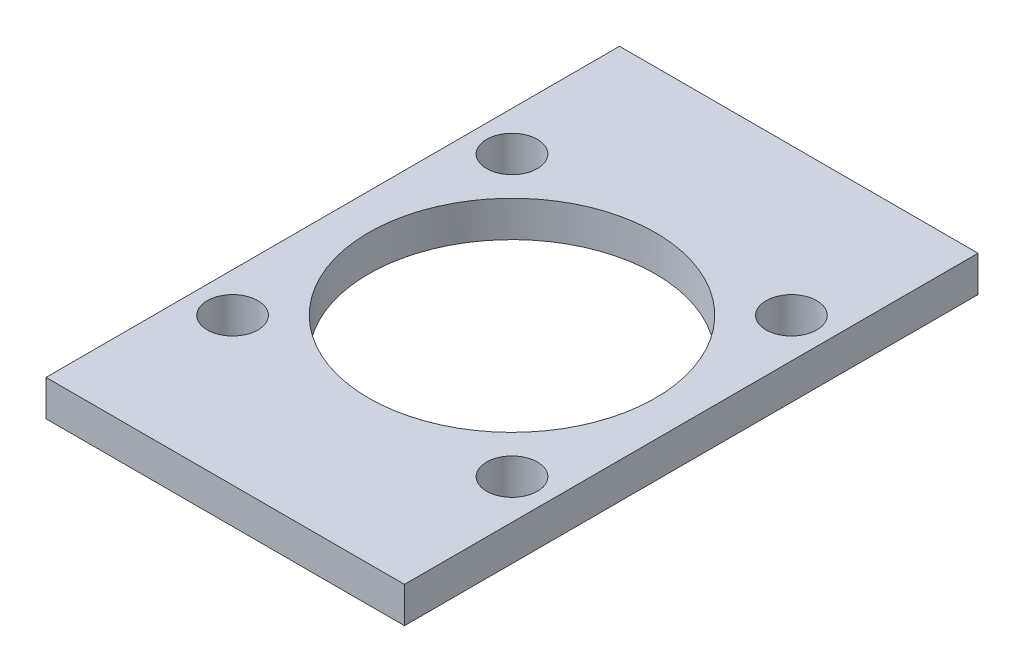
SolidWorks part; units mm, degrees
ref_plane "Front Plane" through (0, 0, 0) normal (0, 0, 1) x (1, 0, 0)
ref_plane "Top Plane" through (0, 0, 0) normal (0, 1, 0) x (1, 0, 0)
ref_plane "Right Plane" through (0, 0, 0) normal (1, 0, 0) x (0, 0, -1)
sketch "Sketch1" plane through (0, 0, 0) normal (0, 1, 0) x (1, 0, 0)
  line L1 (-15.875, -25.4) -> (15.875, -25.4)
  line L2 (-15.875, -25.4) -> (-15.875, 25.4)
  line L3 (-15.875, 25.4) -> (15.875, 25.4)
  line L4 (15.875, -25.4) -> (15.875, 25.4)
  line L5 (-15.875, -25.4) -> (15.875, 25.4) construction
  line L6 (-15.875, 25.4) -> (15.875, -25.4) construction
  point P0 (0, 0)
  dimension "D1" = 31.75
  dimension "D2" = 50.8
extrude "Boss-Extrude1" add sketch "Sketch1" along normal blind 3.175
sketch "Sketch2" plane through (0, 3.175, 0) normal (0, 1, 0) x (1, 0, 0)
  circle A0 centre (0, 0) radius 12.7
  dimension "D1" = 25.4
extrude "Cut-Extrude1" cut sketch "Sketch2" against normal up to next
hole_wizard "M4 Clearance Hole1" positions "Sketch4" profile "Sketch3" hole size "M4" standard "ANSI Metric" end condition up to next
sketch "Sketch4" plane through (0, 3.175, 0) normal (0, 1, 0) x (1, 0, 0)
  circle A0 centre (-12.3748, 12.3748) radius 2.15 construction
  circle A1 centre (12.3748, 12.3748) radius 2.15 construction
  circle A2 centre (-12.3748, -12.3748) radius 2.15 construction
  circle A3 centre (12.3748, -12.3748) radius 2.15 construction
  point P0 (12.3748, -12.3748)
  point P2 (-12.3748, -12.3748)
  point P4 (-12.3748, 12.3748)
  point P6 (12.3748, 12.3748)
sketch "Sketch3" plane through (12.3748, 3.175, 12.3748) normal (1, 0, 0) x (0, 0, 1)
  line L0 (0, 0) -> (0, 3.175)
  line L1 (0, 3.175) -> (2.2479, 3.175)
  line L2 (2.2479, 3.175) -> (2.2479, 0)
  line L5 (2.2479, 0) -> (0, 0)
  line L11 (0, -6.35) -> (0, 107.95) construction
  dimension "Thru Hole Dia." = 4.4958
  dimension "Thru Hole Depth" = 3.175
